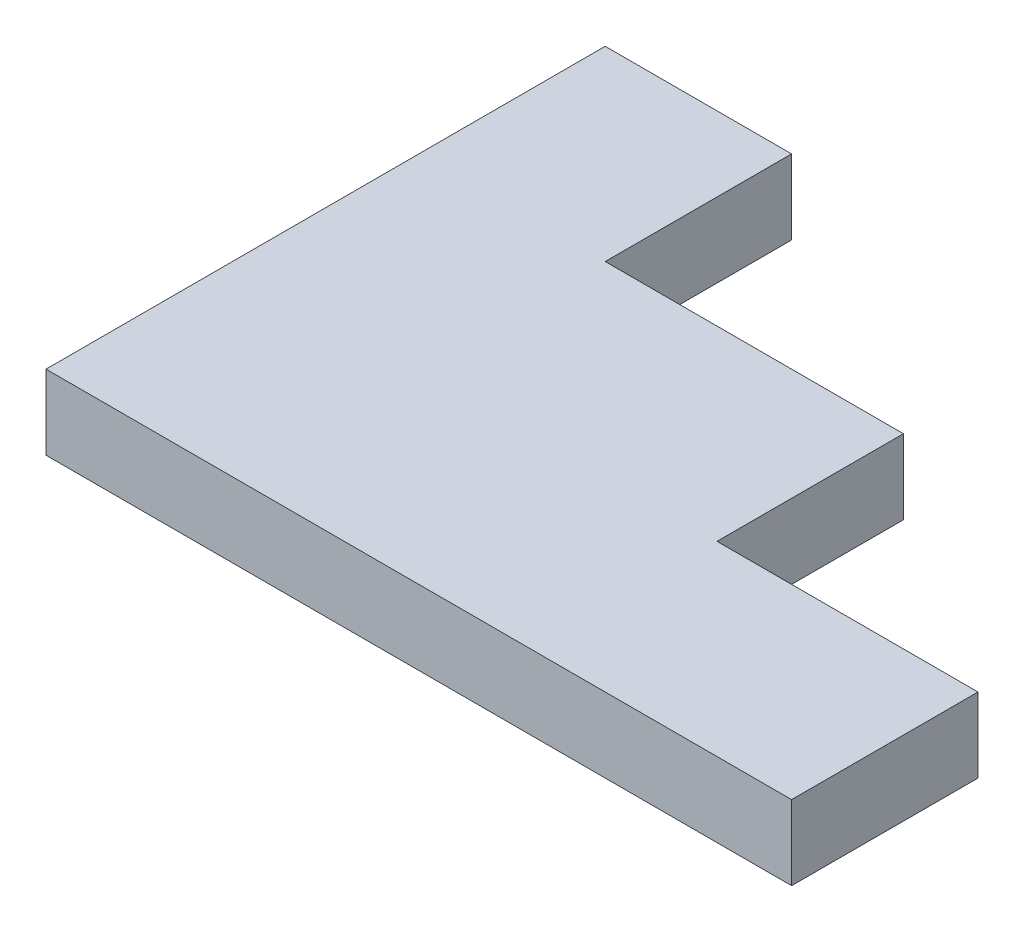
SolidWorks part; units mm, degrees
ref_plane "Front Plane" through (0, 0, 0) normal (0, 0, 1) x (1, 0, 0)
ref_plane "Top Plane" through (0, 0, 0) normal (0, 1, 0) x (1, 0, 0)
ref_plane "Right Plane" through (0, 0, 0) normal (1, 0, 0) x (0, 0, -1)
sketch "Sketch1" plane through (0, 0, 0) normal (0, 1, 0) x (1, 0, 0)
  line L1 (0, 0) -> (20, 0)
  line L2 (0, 0) -> (0, 15)
  line L3 (0, 15) -> (5, 15)
  line L4 (20, 0) -> (20, 5)
  line L6 (5, 15) -> (5, 10)
  line L7 (5, 10) -> (13, 10)
  line L10 (13, 10) -> (13, 5)
  line L11 (13, 5) -> (20, 5)
  dimension "D1" = 20
  dimension "D3" = 10
  dimension "D4" = 15
  dimension "D5" = 5
  dimension "D6" = 8
extrude "Boss-Extrude1" add sketch "Sketch1" along normal blind 2 contours L2 L3 L6 L7 L10 L11 L4 L1
equation "\"A\"= 5"
equation "\"D2@Sketch1\"=\"A\""
